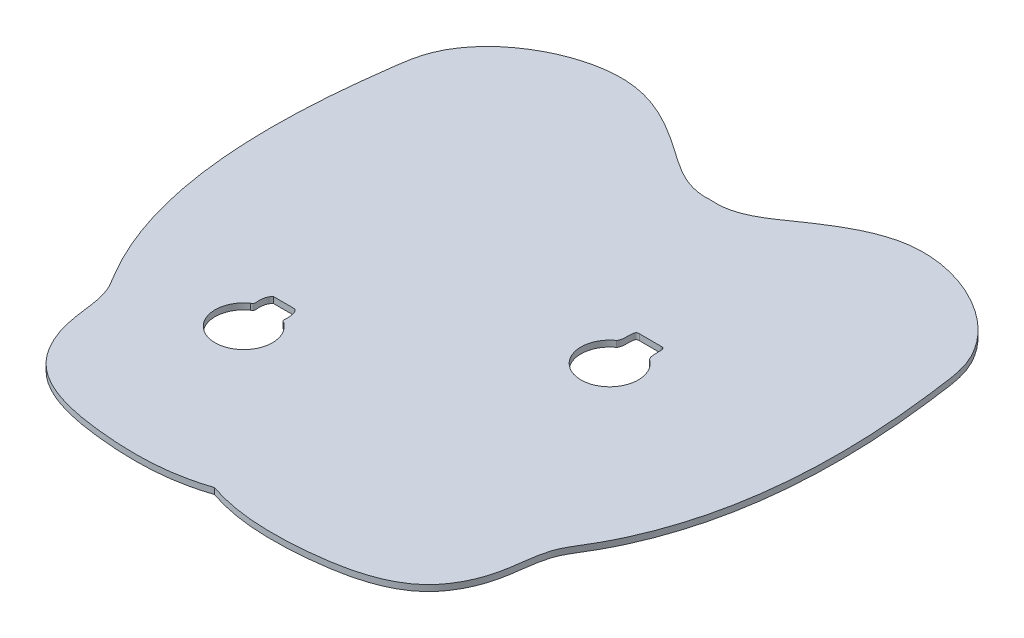
SolidWorks part; units mm, degrees
ref_plane "Front Plane" through (0, 0, 0) normal (0, 0, 1) x (1, 0, 0)
ref_plane "Top Plane" through (0, 0, 0) normal (0, 1, 0) x (1, 0, 0)
ref_plane "Right Plane" through (0, 0, 0) normal (1, 0, 0) x (0, 0, -1)
sketch "Sketch1" plane through (0, 0, 0) normal (0, 1, 0) x (1, 0, 0)
  line L11 (139.5269, -81.8682) -> (135.0997, -81.8682)
  line L15 (130.4716, -81.8682) -> (134.8987, -81.8682)
  line L22 (134.8987, -81.8682) -> (135.0997, -81.8682)
  line L24 (161.5989, -81.8682) -> (166.0261, -81.8682) [skipped]
  line L25 (170.6542, -81.8682) -> (166.227, -81.8682) [skipped]
  line L34 (40.3401, -145.0184) -> (44.7673, -145.0184)
  line L35 (49.3954, -145.0184) -> (44.9682, -145.0184)
  line L36 (44.7673, -145.0184) -> (44.9682, -145.0184)
  arc A17 (128.0139, -89.1108) -> (141.9845, -89.1108) centre (134.9992, -98.8682) ccw
  arc A20 (159.1413, -89.1108) -> (173.1118, -89.1108) centre (166.1265, -98.8682) ccw [skipped]
  arc A23 (37.8825, -152.2611) -> (51.8531, -152.2611) centre (44.8678, -162.0184) ccw
  spline S0 degree 3 poles (37.8825, -152.2611) (39.0151, -152.1397) (38.6503, -150.2681) (38.7672, -147.698) (39.3814, -145.7727) (40.3401, -145.0184) knots 0 0 0 0 0.299147 0.575402 1 1 1 1
  spline S1 degree 3 poles (51.8531, -152.2611) (50.7204, -152.1397) (51.0853, -150.2681) (50.9683, -147.698) (50.3541, -145.7727) (49.3954, -145.0184) knots 0 0 0 0 0.299147 0.575402 1 1 1 1
  spline S8 degree 3 poles (97.1721, -18.4154) (107.4061, -19.2869) (124.8823, -6.0704) (162.3886, 17.2698) (208.5825, -8.2254) (212.3546, -36.8794) (218.5529, -85.5186) (216.5863, -137.4349) (188.947, -180.2685) (189.1642, -197.3448) (176.9344, -224.1557) (138.599, -232.2531) (110.9851, -231.3681) (97.1721, -226.672) knots 0 0 0 0 0.068769 0.160258 0.31161 0.345034 0.370535 0.674249 0.690214 0.741591 0.795466 0.892793 1 1 1 1
  spline S9 degree 3 poles (97.1721, -18.4154) (86.9381, -19.2869) (69.4619, -6.0704) (31.9557, 17.2698) (-14.2383, -8.2254) (-18.0103, -36.8794) (-24.2087, -85.5186) (-22.2421, -137.4349) (5.3972, -180.2685) (5.1801, -197.3448) (17.4099, -224.1557) (55.7453, -232.2531) (83.3592, -231.3681) (97.1721, -226.672) knots 0 0 0 0 0.068769 0.160258 0.31161 0.345034 0.370535 0.674249 0.690214 0.741591 0.795466 0.892793 1 1 1 1
  spline S12 degree 3 poles (141.9845, -89.1108) (141.1267, -88.162) (141.1209, -86.1687) (141.0922, -83.5117) (140.8064, -81.7061) (139.5269, -81.8682) knots 0 0 0 0 0.420984 0.691671 1 1 1 1
  spline S13 degree 3 poles (128.0139, -89.1108) (128.8718, -88.162) (128.8775, -86.1687) (128.9062, -83.5117) (129.1921, -81.7061) (130.4716, -81.8682) knots 0 0 0 0 0.420984 0.691671 1 1 1 1
  dimension "D1" = 2
  dimension "D2" = 2
extrude "Boss-Extrude1" add sketch "Sketch1" along normal blind 2.54
